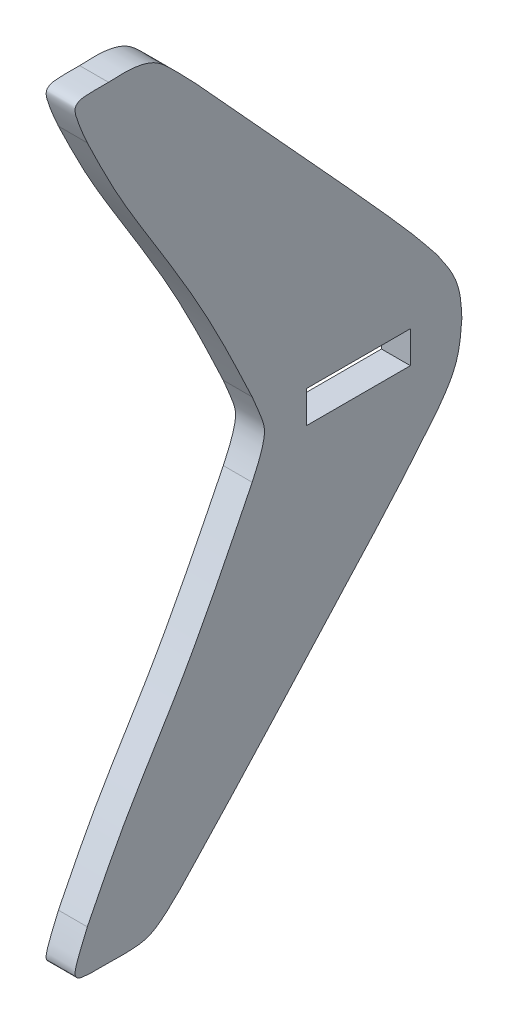
SolidWorks part; units mm, degrees
ref_plane "Alzado" through (0, 0, 0) normal (1, 0, 0) x (0, 1, 0)
ref_plane "Planta" through (0, 0, 0) normal (0, 0, 1) x (0, 1, 0)
ref_plane "Vista lateral" through (0, 0, 0) normal (0, 1, 0) x (-1, 0, 0)
sketch "Croquis1" plane through (0, 0, 0) normal (1, 0, 0) x (0, 1, 0)
  line L0 (15.8686, -7.4516) -> (31.4188, 6.7658)
  line L1 (-1.4432, -3.5886) -> (-1.4432, -13.2886)
  line L2 (-1.4432, -13.2886) -> (1.547, -13.2886)
  line L3 (1.547, -13.2886) -> (1.5568, -3.5886)
  line L4 (1.5568, -3.5886) -> (-1.4432, -3.5886)
  spline S0 degree 3 poles (-0.0401, -18.1027) (-1.202, -18.0098) (-3.5296, -17.8237) (-5.4246, -16.459) (-6.3735, -15.7755) knots 0 0 0 0 0.499172 1 1 1 1
  spline S1 degree 3 poles (-6.3735, -15.7755) (-7.8049, -14.6012) (-11.0756, -11.9179) (-14.1947, -9.0593) (-15.9488, -7.4516) knots 0 0 0 0 0.437615 1 1 1 1
  spline S2 degree 3 poles (-15.9488, -7.4516) (-17.4434, -6.1022) (-20.5304, -3.3149) (-24.7703, 0.5363) (-28.4673, 3.9173) (-30.5547, 5.8786) (-31.4989, 6.7658) knots 0 0 0 0 0.286705 0.592183 0.815537 1 1 1 1
  spline S3 degree 3 poles (-31.4989, 6.7658) (-32.4388, 7.6355) (-33.8944, 8.9824) (-35.5076, 11.0078) (-35.7131, 12.9755) (-35.6877, 14.1943) (-35.6727, 14.9149) knots 0 0 0 0 0.400368 0.620038 0.775371 1 1 1 1
  spline S4 degree 3 poles (-35.6727, 14.9149) (-35.6807, 15.6395) (-35.6909, 16.5654) (-35.5861, 17.634) (-35.2212, 18.1027) (-34.5507, 18.0074) (-33.426, 17.6084) (-32.4722, 17.2005) (-31.7632, 16.8973) knots 0 0 0 0 0.316944 0.405046 0.463446 0.551891 0.666909 1 1 1 1
  spline S5 degree 3 poles (-31.7632, 16.8973) (-29.5258, 15.7813) (-24.5417, 13.2952) (-15.5273, 7.4293) (-8.132, 3.7807) (-3.4903, 1.4906) knots 0 0 0 0 0.232718 0.518418 1 1 1 1
  spline S6 degree 3 poles (-3.4903, 1.4906) (-2.7391, 1.1467) (-1.5524, 0.6035) (0.2066, 0.2182) (1.747, 0.7888) (2.7742, 1.2223) (3.4102, 1.4906) knots 0 0 0 0 0.341131 0.538893 0.714558 1 1 1 1
  spline S7 degree 3 poles (3.4102, 1.4906) (6.3922, 2.8951) (12.3104, 5.6824) (19.8462, 10.3087) (26.1812, 14.2337) (29.9673, 16.0667) (31.683, 16.8973) knots 0 0 0 0 0.306659 0.608596 0.822631 1 1 1 1
  spline S8 degree 3 poles (31.683, 16.8973) (32.5133, 17.2637) (33.54, 17.7167) (34.7195, 18.0632) (35.2073, 18.0277) (35.5036, 17.6325) (35.6135, 16.5673) (35.6018, 15.6403) (35.5926, 14.9149) knots 0 0 0 0 0.394573 0.487867 0.536934 0.595286 0.683316 1 1 1 1
  spline S9 degree 3 poles (35.5926, 14.9149) (35.6372, 14.0398) (35.7131, 12.5503) (35.1, 10.4246) (33.4404, 8.7041) (32.1938, 7.5089) (31.4188, 6.7658) knots 0 0 0 0 0.271148 0.461498 0.665175 1 1 1 1
  spline S10 degree 3 poles (15.8686, -7.4516) (14.6608, -8.5396) (12.5284, -10.4603) (9.3865, -13.2944) (7.3545, -14.9243) (6.2934, -15.7755) knots 0 0 0 0 0.384323 0.678495 1 1 1 1
  spline S11 degree 3 poles (6.2934, -15.7755) (5.122, -16.5936) (3.1941, -17.9399) (0.8713, -18.0569) (-0.0401, -18.1027) knots 0 0 0 0 0.607668 1 1 1 1
  point P0 (1.5519, -8.4386)
  dimension "D1" = 35
  dimension "D2" = 9.7
  dimension "D3" = 3
extrude "Saliente-Extruir1" add sketch "Croquis1" along normal blind 2.7 contours S11 S10 L0 S9 S8 S7 S6 S5 S4 S3 S2 S1 S0 L4 L3 L2 L1
